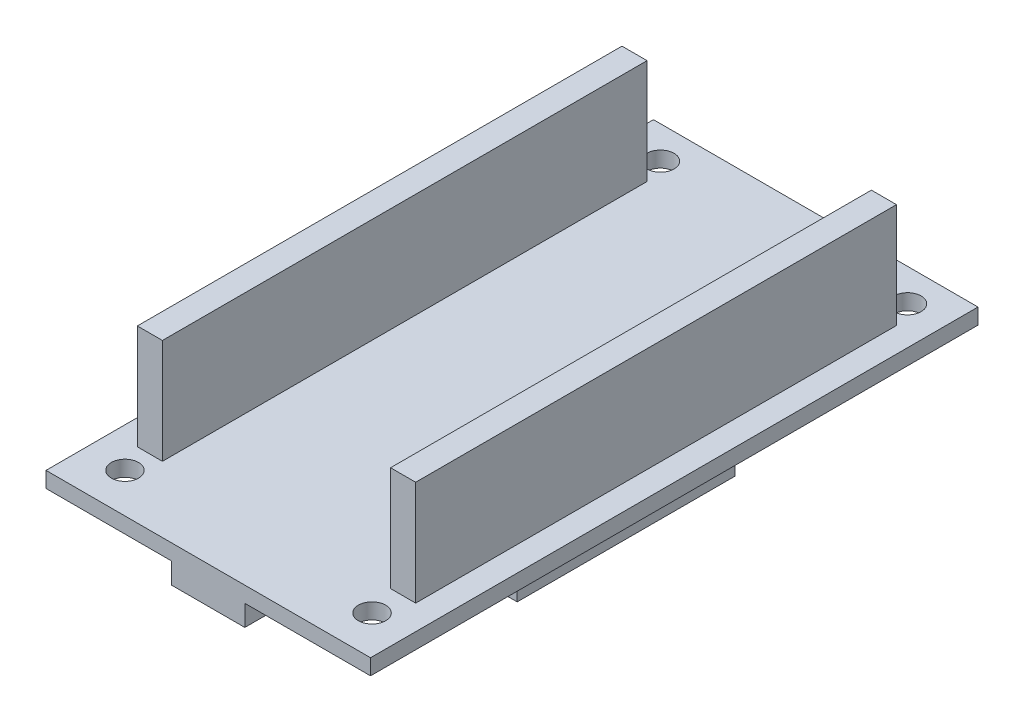
SolidWorks part; units mm, degrees
ref_plane "Front Plane" through (0, 0, 0) normal (0, 0, 1) x (1, 0, 0)
ref_plane "Top Plane" through (0, 0, 0) normal (0, 1, 0) x (1, 0, 0)
ref_plane "Right Plane" through (0, 0, 0) normal (1, 0, 0) x (0, 0, -1)
sketch "Sketch1" plane through (0, 0, 0) normal (0, 1, 0) x (1, 0, 0)
  line L1 (-3.7666, 54.2482) -> (27.2347, 54.2482)
  line L2 (-3.7666, 54.2482) -> (-3.7666, -3.7775)
  line L3 (-3.7666, -3.7775) -> (27.2347, -3.7775)
  line L4 (27.2347, 54.2482) -> (27.2347, -3.7775)
  circle A0 centre (0, 0) radius 1.3
  circle A1 centre (23.6, 0) radius 1.3
  circle A2 centre (23.6, 51.15) radius 1.3
  circle A3 centre (0, 51.15) radius 1.3
  dimension "D1" = 2.6
  dimension "D2" = 2
  dimension "D3" = 2
extrude "Boss-Extrude1" add sketch "Sketch1" along normal blind 1.5
sketch "Sketch2" plane through (0, 0, 0) normal (0, -1, 0) x (-1, 0, 0)
  line L0 (3.7666, -3.7775) -> (-27.2347, -3.7775) construction
  line L1 (-8.2411, -3.7775) -> (-15.227, -3.7775)
  line L2 (-8.2411, -3.7775) -> (-8.2411, 3.626)
  line L3 (-8.2411, 3.626) -> (-15.227, 3.626)
  line L4 (-15.227, -3.7775) -> (-15.227, 3.626)
extrude "Boss-Extrude2" add sketch "Sketch2" along normal blind 2
sketch "Sketch3" plane through (0, 1.5, 0) normal (0, 1, 0) x (1, 0, 0)
  line L1 (-1.3515, 48.8258) -> (1.0467, 48.8258)
  line L2 (-1.3515, 48.8258) -> (-1.3515, 2.5312)
  line L3 (-1.3515, 2.5312) -> (1.0467, 2.5312)
  line L4 (1.0467, 48.8258) -> (1.0467, 2.5312)
  line L5 (22.4735, 48.8258) -> (24.8717, 48.8258)
  line L6 (22.4735, 48.8258) -> (22.4735, 2.8962)
  line L7 (22.4735, 2.8962) -> (24.8717, 2.8962)
  line L8 (24.8717, 48.8258) -> (24.8717, 2.8962)
extrude "Boss-Extrude3" add sketch "Sketch3" along normal blind 10
sketch "Sketch4" plane through (0, 0, 0) normal (0, -1, 0) x (-1, 0, 0)
  line L1 (-26.1229, 11.3418) -> (-24.4546, 11.3418)
  line L2 (-26.1229, 11.3418) -> (-26.1229, 32.1431)
  line L3 (-26.1229, 32.1431) -> (-24.4546, 32.1431)
  line L4 (-24.4546, 11.3418) -> (-24.4546, 32.1431)
extrude "Boss-Extrude4" add sketch "Sketch4" along normal blind 2
